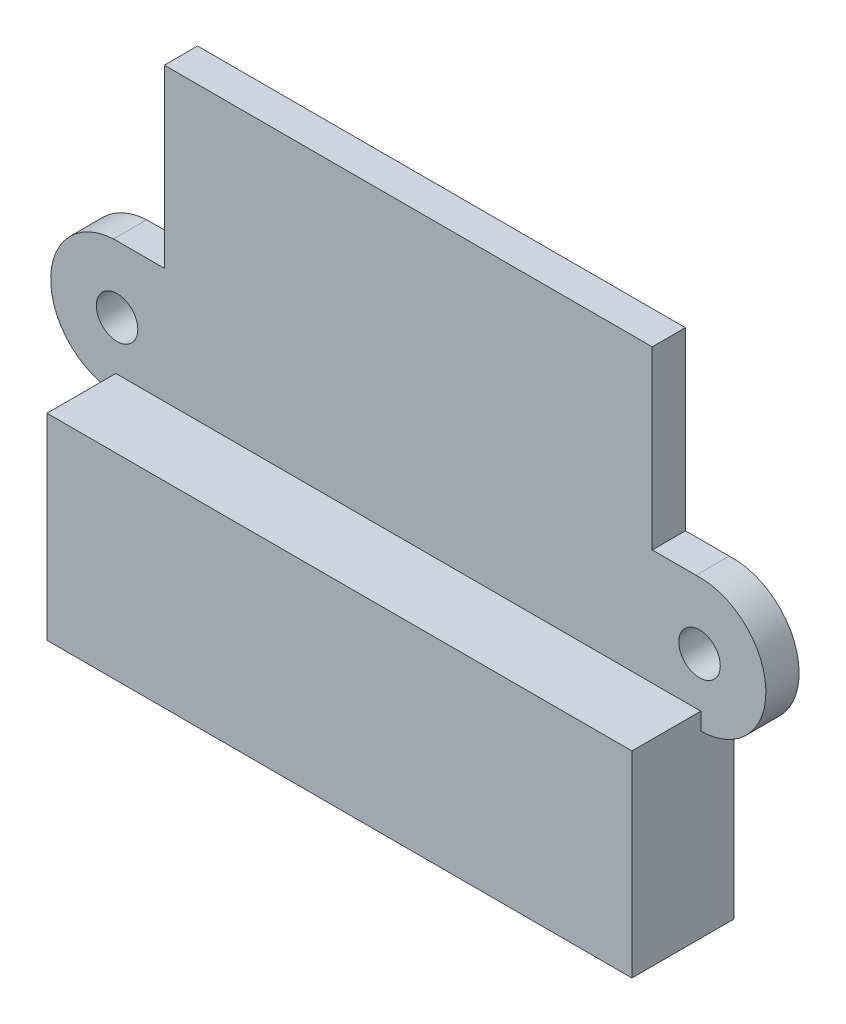
SolidWorks part; units mm, degrees
ref_plane "Front Plane" through (0, 0, 0) normal (0, 0, 1) x (1, 0, 0)
ref_plane "Top Plane" through (0, 0, 0) normal (0, 1, 0) x (1, 0, 0)
ref_plane "Right Plane" through (0, 0, 0) normal (1, 0, 0) x (0, 0, -1)
sketch "Sketch1" plane through (0, 0, 0) normal (0, 0, 1) x (1, 0, 0)
  line L0 (0, 7.4676) -> (0, -7.4676) construction
  line L1 (-7.4676, 7.4676) -> (7.4676, 7.4676)
  line L2 (-7.4676, 7.4676) -> (-7.4676, 2.0828)
  line L3 (-8.9535, -7.4676) -> (8.9535, -7.4676)
  line L4 (7.4676, 7.4676) -> (7.4676, 2.0828)
  line L5 (8.9535, -1.978) -> (8.9535, -7.4676)
  line L6 (7.4676, 2.0828) -> (8.8086, 2.0828)
  line L7 (-8.9535, -1.978) -> (-8.9535, -7.4676)
  line L10 (-7.4676, 2.0828) -> (-9.0222, 2.0828)
  arc A0 (8.9535, -1.978) -> (8.8086, 2.0828) centre (8.9154, 0.0536) ccw
  arc A1 (-9.0222, 2.0828) -> (-8.9535, -1.978) centre (-8.9154, 0.0536) ccw
  circle A2 centre (-8.9154, 0.0536) radius 0.635
  circle A3 centre (8.9154, 0.0536) radius 0.635
  dimension "D7" = 17.8308
  dimension "D9" = 2.032
  dimension "D10" = 2.032
  dimension "D12" = 1.27
  dimension "D13" = 1.27
  dimension "D4" = 7.5212
  dimension "D1" = 14.9352
  dimension "D2" = 14.9352
  dimension "D3" = 5.3848
  dimension "D5" = 5.3848
  dimension "D8" = 1.4478
  dimension "D11" = 1.4478
  dimension "D14" = 17.907
extrude "Boss-Extrude1" add sketch "Sketch1" along normal blind 1.016 contours L4 L6 A0 L5 L3 L7 A1 L10 L2 L1 | A2 | A3
sketch "Sketch2" plane through (0, 0, 1.016) normal (0, 0, 1) x (1, 0, 0)
  line L0 (8.9535, -1.978) -> (8.9535, -7.4676) construction
  line L1 (-8.9535, -7.4676) -> (8.9535, -7.4676)
  line L2 (-8.9535, -7.4676) -> (-8.9535, -1.4478)
  line L3 (-8.9535, -1.4478) -> (8.9535, -1.4478)
  line L4 (8.9535, -7.4676) -> (8.9535, -1.4478)
  line L5 (-7.4676, 7.4676) -> (7.4676, 7.4676) construction
  dimension "D1" = 8.9154
extrude "Boss-Extrude2" add sketch "Sketch2" along normal blind 2.1082
